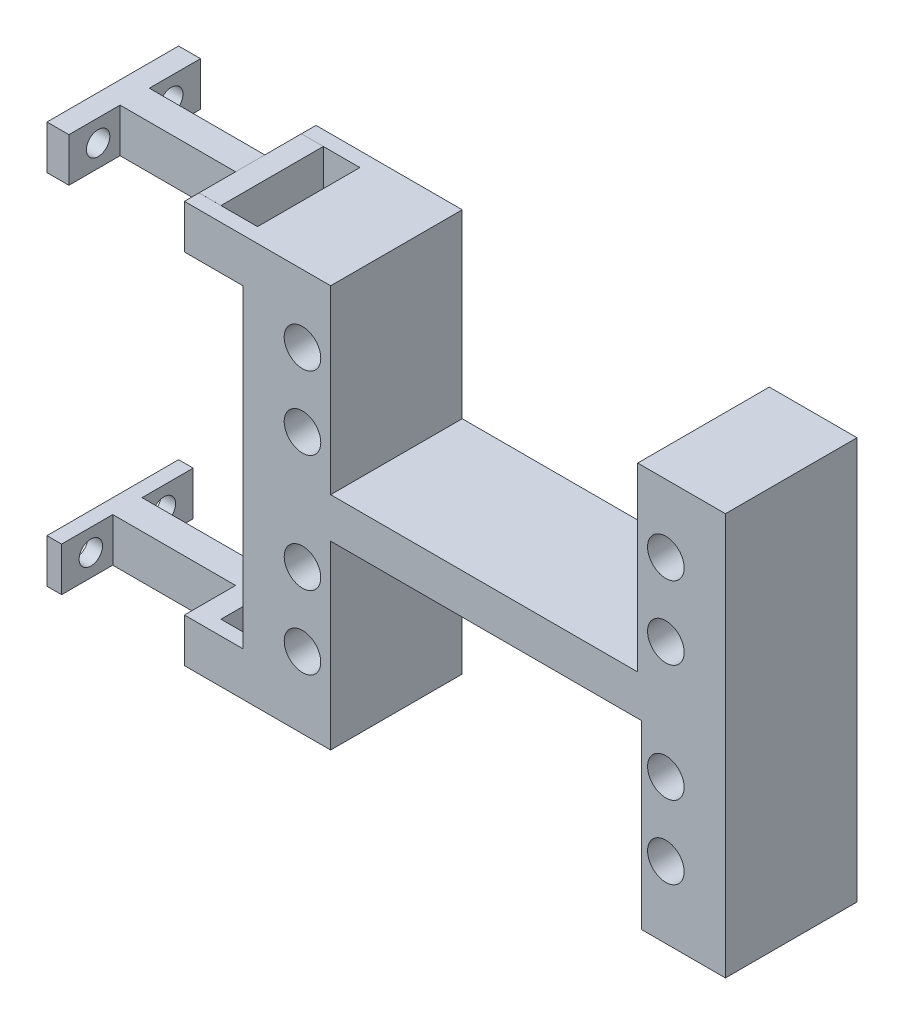
SolidWorks part; units mm, degrees
ref_plane "Front Plane" through (0, 0, 0) normal (0, 0, 1) x (1, 0, 0)
ref_plane "Top Plane" through (0, 0, 0) normal (0, 1, 0) x (1, 0, 0)
ref_plane "Right Plane" through (0, 0, 0) normal (1, 0, 0) x (0, 0, -1)
sketch "Sketch2" plane through (0, 0, 0) normal (0, 0, 1) x (1, 0, 0)
  line L0 (0, -55) -> (0, 55) construction
  line L1 (0, 55) -> (66, 55)
  line L2 (0, 55) -> (0, 0)
  line L3 (0, 0) -> (66, 0)
  line L4 (66, 55) -> (66, 0)
  line L5 (55, 0) -> (-55, 0) construction
  line L7 (12, 50.75) -> (54, 50.75)
  line L8 (12, 50.75) -> (12, 30.25)
  line L9 (12, 30.25) -> (54, 30.25)
  line L10 (54, 50.75) -> (54, 30.25)
  line L11 (12, 24.75) -> (54.5, 24.75)
  line L12 (12, 24.75) -> (12, 4.25)
  line L13 (12, 4.25) -> (54.5, 4.25)
  line L14 (54.5, 24.75) -> (54.5, 4.25)
  dimension "D1" = 55
  dimension "D2" = 12
  dimension "D3" = 42
  dimension "D4" = 20.5
  dimension "D5" = 5.5
  dimension "D6" = 42.5
  dimension "D7" = 20.5
  dimension "D8" = 12
  dimension "D9" = 4.25
  dimension "D10" = 12
extrude "Boss-Extrude1" add sketch "Sketch2" along normal blind 18
sketch "Sketch3" plane through (0, 0, 18) normal (0, 0, 1) x (1, 0, 0)
  line L0 (54, 50.75) -> (12, 50.75) construction
  line L1 (12, 50.75) -> (12, 30.25) construction
  line L2 (12, 24.75) -> (12, 4.25) construction
  line L3 (54.5, 24.75) -> (12, 24.75) construction
  circle A0 centre (8.15, 45.75) radius 2.5
  circle A1 centre (8.15, 35.75) radius 2.5
  circle A6 centre (57.85, 35.75) radius 2.5
  circle A7 centre (57.85, 45.75) radius 2.5
  circle A8 centre (8.15, 19.75) radius 2.5
  circle A9 centre (8.15, 9.75) radius 2.5
  circle A10 centre (57.85, 9.75) radius 2.5
  circle A11 centre (57.85, 19.75) radius 2.5
  dimension "D1" = 10
  dimension "D2" = 5
  dimension "D3" = 5
  dimension "D4" = 5
  dimension "D5" = 3.85
  dimension "D6" = 3.85
  dimension "D7" = 45.85
  dimension "D8" = 45.85
  dimension "D9" = 45.85
  dimension "D10" = 45.85
  dimension "D11" = 5
  dimension "D12" = 5
  dimension "D13" = 3.85
  dimension "D14" = 3.85
  dimension "D15" = 10
  dimension "D16" = 5
  dimension "D17" = 5
  dimension "D18" = 5
  dimension "D19" = 5
  dimension "D20" = 5
  dimension "D21" = 5
  dimension "D22" = 5
  dimension "D23" = 10
  dimension "D24" = 10
extrude "Cut-Extrude1" cut sketch "Sketch3" against normal blind 10
sketch "Sketch5" plane through (0, 0, 0) normal (-1, 0, 0) x (0, 0, 1)
  line L0 (0, -55) -> (0, 55) construction
  line L1 (0, 55) -> (2, 55)
  line L2 (0, 55) -> (0, 49)
  line L3 (0, 49) -> (2, 49)
  line L4 (2, 55) -> (2, 49)
  line L5 (18, 55) -> (0, 55) construction
  line L6 (55, 0) -> (-55, 0) construction
  line L7 (18, 55) -> (16, 55)
  line L8 (18, 55) -> (18, 49)
  line L9 (18, 49) -> (16, 49)
  line L10 (16, 55) -> (16, 49)
  line L11 (0, 0) -> (2, 0)
  line L12 (0, 0) -> (0, 6)
  line L13 (0, 6) -> (2, 6)
  line L14 (2, 0) -> (2, 6)
  line L15 (18, 0) -> (16, 0)
  line L16 (18, 0) -> (18, 6)
  line L17 (18, 6) -> (16, 6)
  line L18 (16, 0) -> (16, 6)
  line L19 (18, 55) -> (18, 0) construction
  dimension "D1" = 2
  dimension "D2" = 2
  dimension "D3" = 6
  dimension "D4" = 6
  dimension "D5" = 2
  dimension "D6" = 2
  dimension "D7" = 6
  dimension "D8" = 6
extrude "Boss-Extrude2" add sketch "Sketch5" along normal blind 26.8
sketch "Sketch6" plane through (0, 0, 2) normal (0, 0, 1) x (1, 0, 0)
  line L0 (-26.8, 49) -> (0, 49) construction
  line L1 (-23.8, 49) -> (-26.8, 49)
  line L2 (-23.8, 49) -> (-23.8, 55)
  line L3 (-23.8, 55) -> (-26.8, 55)
  line L4 (-26.8, 49) -> (-26.8, 55)
  line L5 (66, 55) -> (-26.8, 55) construction
  line L6 (-26.8, 55) -> (-26.8, 49) construction
  line L7 (9.9, 0) -> (-9.9, 0) construction
  line L8 (-26.8, 6) -> (-24.8, 6)
  line L9 (-26.8, 6) -> (-26.8, 0)
  line L10 (-26.8, 0) -> (-24.8, 0)
  line L11 (-24.8, 6) -> (-24.8, 0)
  dimension "D1" = 3
  dimension "D2" = 2
extrude "Boss-Extrude3" add sketch "Sketch6" along normal up to next
sketch "Sketch7" plane through (-26.8, 0, 0) normal (-1, 0, 0) x (0, 0, 1)
  line L0 (0, -30.25) -> (0, 30.25) construction
  line L1 (18, 55) -> (0, 55) construction
  line L2 (18, 49) -> (18, 55) construction
  line L3 (18, 0) -> (18, 6) construction
  line L4 (18, 6) -> (0, 6) construction
  circle A0 centre (4, 52) radius 1.6
  circle A1 centre (14, 52) radius 1.6
  circle A2 centre (4, 3) radius 1.6
  circle A3 centre (14, 3) radius 1.6
  dimension "D1" = 3.2
  dimension "D2" = 3.2
  dimension "D3" = 4
  dimension "D4" = 3
  dimension "D5" = 4
  dimension "D6" = 3
  dimension "D7" = 3.2
  dimension "D8" = 3.2
  dimension "D9" = 4
  dimension "D10" = 4
  dimension "D11" = 3
  dimension "D12" = 3
extrude "Cut-Extrude2" cut sketch "Sketch7" against normal blind 10
sketch "Sketch8" plane through (0, 0, 18) normal (0, 0, 1) x (1, 0, 0)
  line L0 (66, 55) -> (-26.8, 55) construction
  line L1 (12, 50.75) -> (54, 50.75)
  line L2 (12, 50.75) -> (12, 55)
  line L3 (12, 55) -> (54, 55)
  line L4 (54, 50.75) -> (54, 55)
  line L5 (9.9, 0) -> (-9.9, 0) construction
  line L6 (12, 4.25) -> (54.5, 4.25)
  line L7 (12, 4.25) -> (12, 0)
  line L8 (12, 0) -> (54.5, 0)
  line L9 (54.5, 4.25) -> (54.5, 0)
extrude "Cut-Extrude3" cut sketch "Sketch8" against normal up to next
sketch "Sketch9" plane through (0, 0, 2) normal (0, 0, 1) x (1, 0, 0)
  line L0 (0, 49) -> (0, 55) construction
  line L1 (-8, 55.0022) -> (-5, 55.0022)
  line L2 (-8, 55.0022) -> (-8, 49.0022)
  line L3 (-8, 49.0022) -> (-5, 49.0022)
  line L4 (-5, 55.0022) -> (-5, 49.0022)
  dimension "D1" = 5
  dimension "3" = 3
  dimension "D2" = 6
extrude "Boss-Extrude5" add sketch "Sketch9" along normal up to surface (14 mm away) up to face at (-11.9, 52, 16)
sketch "Sketch10" plane through (0, 0, 16) normal (0, 0, -1) x (-1, 0, 0)
  line L2 (8, 55.0022) -> (23.8, 55.0022)
  line L3 (8, 55.0022) -> (8, 49)
  line L4 (8, 49) -> (23.8, 49)
  line L5 (23.8, 55.0022) -> (23.8, 49)
extrude "Cut-Extrude4" cut sketch "Sketch10" against normal blind 10 and the other way blind 21
sketch "Sketch11" plane through (-8, 0, 0) normal (-1, 0, 0) x (0, 0, 1)
  line L0 (18, 55) -> (0, 55) construction
  line L1 (7, 55) -> (11, 55)
  line L2 (7, 55) -> (7, 49)
  line L3 (7, 49) -> (11, 49)
  line L4 (11, 55) -> (11, 49)
  line L5 (0, 49) -> (18, 49) construction
  line L6 (0, -30.2512) -> (0, 30.2512) construction
  line L7 (18, 49) -> (18, 55) construction
  dimension "D1" = 7
  dimension "D2" = 7
extrude "Boss-Extrude6" add sketch "Sketch11" along normal up to surface (15.8 mm away) up to face at (-23.8, 52, 15.6)
sketch "Sketch12" plane through (0, 0, 2) normal (0, 0, 1) x (1, 0, 0)
  line L0 (-26.8, 6) -> (0, 6) construction
  line L1 (-8, 6) -> (-5, 6)
  line L2 (-8, 6) -> (-8, 0)
  line L3 (-8, 0) -> (-5, 0)
  line L4 (-5, 6) -> (-5, 0)
  line L5 (9.9, 0) -> (-9.9, 0) construction
  line L6 (0, -9.9) -> (0, 9.9) construction
  dimension "D1" = 3
  dimension "D2" = 5
extrude "Boss-Extrude7" add sketch "Sketch12" along normal up to surface (14 mm away) up to face at (-12.4, 3, 16)
sketch "Sketch13" plane through (0, 0, 16) normal (0, 0, -1) x (-1, 0, 0)
  line L1 (8, 6) -> (24.8, 6)
  line L2 (8, 6) -> (8, 0)
  line L3 (8, 0) -> (24.8, 0)
  line L4 (24.8, 6) -> (24.8, 0)
extrude "Cut-Extrude5" cut sketch "Sketch13" against normal blind 10 and the other way blind 18
sketch "Sketch14" plane through (-8, 0, 0) normal (-1, 0, 0) x (0, 0, 1)
  line L0 (18, 6) -> (0, 6) construction
  line L1 (7, 6) -> (11, 6)
  line L2 (7, 6) -> (7, 0)
  line L3 (7, 0) -> (11, 0)
  line L4 (11, 6) -> (11, 0)
  line L5 (9.9, 0) -> (-9.9, 0) construction
  line L6 (0, -30.2512) -> (0, 30.2512) construction
  line L7 (18, 0) -> (18, 6) construction
  dimension "D1" = 7
  dimension "D2" = 7
extrude "Boss-Extrude8" add sketch "Sketch14" along normal up to surface (16.8 mm away) up to face at (-24.8, 3, 5.6)
